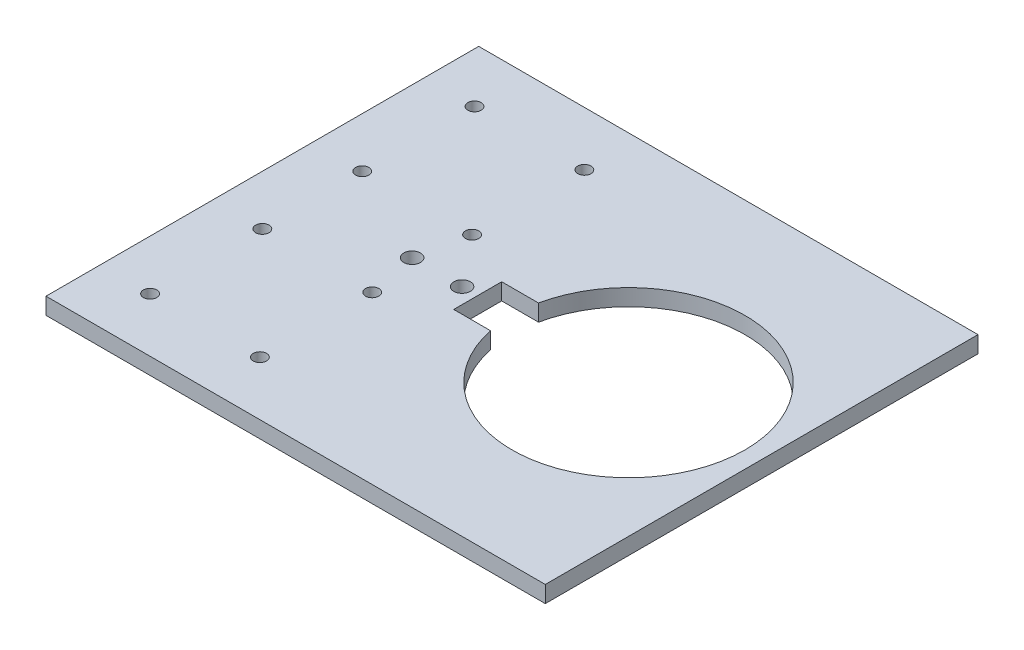
SolidWorks part; units mm, degrees
ref_plane "Front Plane" through (0, 0, 0) normal (0, 0, 1) x (1, 0, 0)
ref_plane "Top Plane" through (0, 0, 0) normal (0, 1, 0) x (1, 0, 0)
ref_plane "Right Plane" through (0, 0, 0) normal (1, 0, 0) x (0, 0, -1)
sketch "Sketch1" plane through (0, 0, 0) normal (0, 1, 0) x (1, 0, 0)
  line L0 (0.7506, -7.2095) -> (-10.3057, -7.2095)
  line L1 (-75, -65) -> (75, -65)
  line L2 (-75, -65) -> (-75, 65)
  line L3 (-75, 65) -> (75, 65)
  line L4 (75, -65) -> (75, 65)
  line L5 (-75, -65) -> (-8.3186, -7.2095) construction
  line L6 (-75, 65) -> (-8.3186, 7.2095) construction
  line L10 (-10.3057, -7.2095) -> (-10.3057, 7.2095)
  line L11 (-35, 0) -> (-75, 0) construction
  line L15 (0.7506, 7.2095) -> (-10.3057, 7.2095)
  line L16 (39.9746, 34.6447) -> (75, 65) construction
  line L17 (39.9746, -34.6447) -> (75, -65) construction
  arc A0 (0.7506, -7.2095) -> (0.7506, 7.2095) centre (35, 0) ccw
  circle A1 centre (-15, 0) radius 2.5
  circle A2 centre (-30, 0) radius 2.5
  circle A3 centre (-60, -15) radius 2
  circle A4 centre (-60, -48.7378) radius 2
  circle A5 centre (-27, -48.7378) radius 2
  circle A6 centre (-27, -15) radius 2
  circle A7 centre (-27, 15) radius 2
  circle A8 centre (-60, 15) radius 2
  circle A9 centre (-60, 48.7378) radius 2
  circle A10 centre (-27, 48.7378) radius 2
  point P0 (0, 0)
  point P8 (0, 0)
  dimension "D3" = 70
  dimension "D12" = 15
  dimension "D13" = 15
  dimension "D14" = 15
  dimension "D15" = 15
  dimension "D1" = 130
  dimension "D2" = 150
  dimension "D4" = 40
  dimension "D5" = 0
  dimension "D6" = 33.7378
  dimension "D7" = 33.7378
  dimension "D8" = 33.7378
  dimension "D9" = 33.7378
  dimension "D10" = 33
  dimension "D11" = 33
extrude "Boss-Extrude1" add sketch "Sketch1" along normal blind 5
